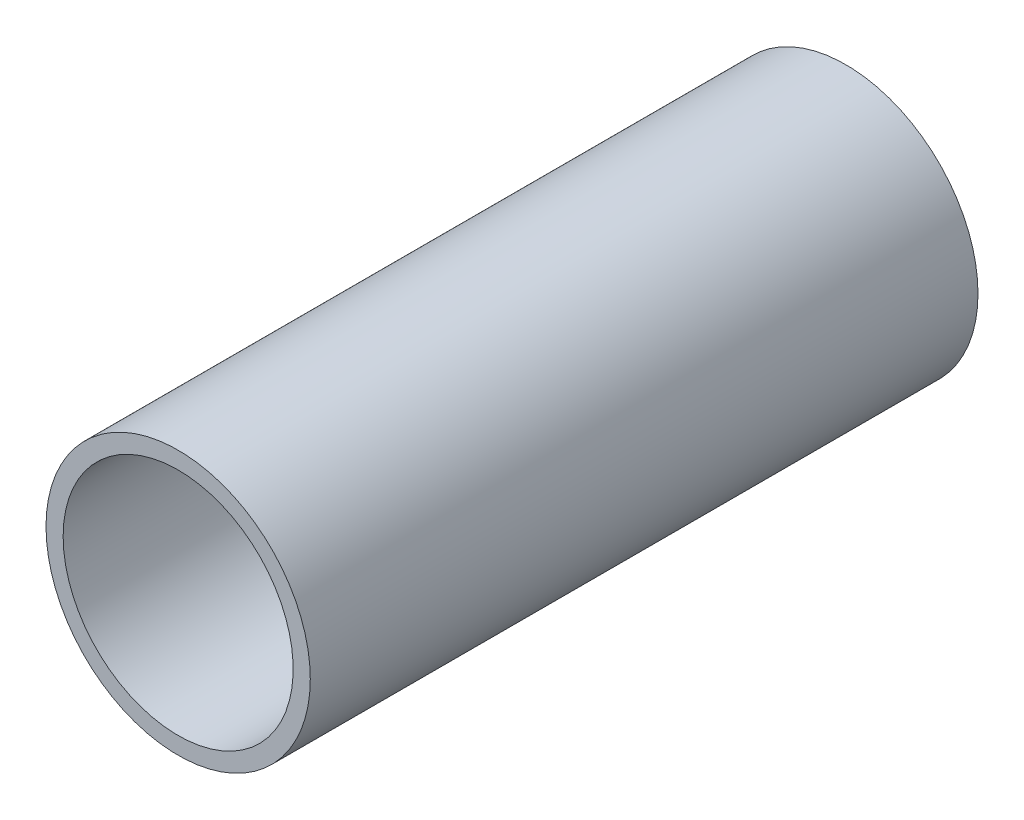
SolidWorks part; units mm, degrees
ref_plane "Front Plane" through (0, 0, 0) normal (0, 0, 1) x (1, 0, 0)
ref_plane "Top Plane" through (0, 0, 0) normal (0, 1, 0) x (1, 0, 0)
ref_plane "Right Plane" through (0, 0, 0) normal (1, 0, 0) x (0, 0, -1)
sketch "Sketch1" plane through (0, 0, 0) normal (0, 0, 1) x (1, 0, 0)
  circle A0 centre (0, 0) radius 30.1625
  circle A1 centre (0, 0) radius 26.2509
  dimension "D1" = 60.325
  dimension "D2" = 3.9116
extrude "Boss-Extrude1" add sketch "Sketch1" along normal blind 152.4
